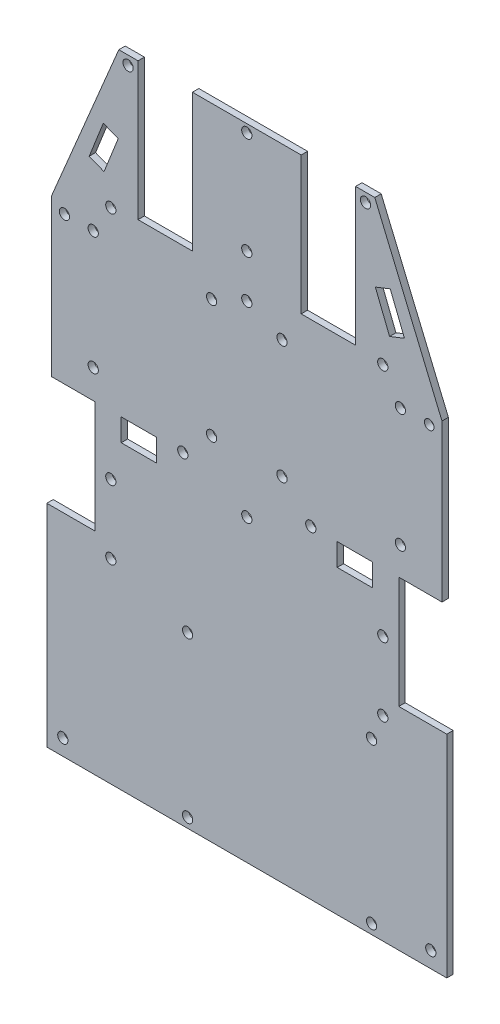
SolidWorks part; units mm, degrees
ref_plane "前基準面" through (0, 0, 0) normal (0, 0, 1) x (1, 0, 0)
ref_plane "上基準面" through (0, 0, 0) normal (0, 1, 0) x (1, 0, 0)
ref_plane "右基準面" through (0, 0, 0) normal (1, 0, 0) x (0, 0, -1)
sketch "草圖1" plane through (0, 0, 0) normal (0, 0, 1) x (1, 0, 0)
  line L0 (-42.5, 0) -> (42.5, 0)
  line L1 (-42.5, 0) -> (-42.5, 56)
  line L2 (-42.5, 56) -> (42.5, 56)
  line L3 (42.5, 56) -> (42.5, 0)
  line L4 (42.5, 0) -> (62.5, 0)
  line L5 (-42.5, 0) -> (-62.5, 0)
  line L6 (-62.5, 0) -> (-62.5, 66)
  line L7 (62.5, 0) -> (62.5, 66)
  line L8 (-62.5, 66) -> (-47.5, 66)
  line L9 (62.5, 66) -> (47.5, 66)
  line L10 (-47.5, 66) -> (-47.5, 101)
  line L12 (47.5, 101) -> (47.5, 66)
  line L16 (-62.5, 0) -> (-90.3643, 0)
  line L17 (-90.3643, 0) -> (-90.3643, 200)
  line L18 (-47.5, 101) -> (-61, 101)
  line L19 (47.5, 101) -> (61, 101)
  line L28 (-61, 101) -> (-61, 150)
  line L29 (-39.25, 101) -> (-28.25, 101)
  line L30 (39.25, 94) -> (28.25, 94)
  line L31 (-39.25, 101) -> (-39.25, 94)
  line L32 (-39.25, 94) -> (-28.25, 94)
  line L33 (-28.25, 101) -> (-28.25, 94)
  line L34 (28.25, 101) -> (28.25, 94)
  line L35 (39.25, 101) -> (28.25, 101)
  line L36 (39.25, 101) -> (39.25, 94)
  line L37 (61, 101) -> (61, 150)
  line L38 (62.5, 0) -> (90.3643, 0)
  line L39 (90.3643, 0) -> (90.3643, 200)
  line L40 (51, 107) -> (8, 107)
  line L41 (-51, 150) -> (-8, 150)
  line L42 (34, 200) -> (40, 200)
  line L43 (-51, 150) -> (-51, 107)
  line L44 (-51, 107) -> (-8, 107)
  line L45 (-8, 150) -> (-8, 107)
  line L46 (8, 150) -> (8, 107)
  line L47 (51, 150) -> (8, 150)
  line L48 (51, 150) -> (51, 107)
  line L49 (-17, 157) -> (-17, 200)
  line L50 (17, 157) -> (17, 200)
  line L52 (17, 157) -> (34, 157)
  line L53 (34, 157) -> (34, 200)
  line L54 (40, 200) -> (61, 150)
  line L55 (-90.3643, 200) -> (-40, 200)
  line L56 (-40, 200) -> (-61, 150)
  line L57 (-34, 200) -> (-40, 200)
  line L58 (-34, 157) -> (-34, 200)
  line L59 (-17, 157) -> (-34, 157)
  line L60 (-34, 200) -> (34, 200)
  line L62 (40, 200) -> (90.3643, 200)
  line L80 (62.5, 0) -> (62.5, -5)
  line L81 (-37.0994, 197.2091) -> (-56.9967, 147.0085) construction
  line L82 (37.0994, 197.2091) -> (56.9967, 147.0085) construction
  line L83 (-40.189, 175.8443) -> (-44.6106, 164.6886)
  line L84 (-40.189, 175.8443) -> (-44.8372, 177.6866)
  line L85 (-44.6106, 164.6886) -> (-49.2588, 166.5309)
  line L86 (-49.2588, 166.5309) -> (-44.8372, 177.6866)
  line L91 (40.189, 175.8443) -> (44.6106, 164.6886)
  line L92 (44.6106, 164.6886) -> (49.2588, 166.5309)
  line L93 (40.189, 175.8443) -> (44.8372, 177.6866)
  line L94 (44.8372, 177.6866) -> (49.2588, 166.5309)
  circle A0 centre (-48, 147) radius 1.6
  circle A1 centre (-48, 110) radius 1.6
  circle A2 centre (-11, 147) radius 1.6
  circle A3 centre (-11, 110) radius 1.6
  circle A4 centre (11, 147) radius 1.6
  circle A5 centre (47.9967, 147) radius 1.6
  circle A6 centre (47.9967, 110) radius 1.6
  circle A7 centre (11, 110) radius 1.6
  circle A10 centre (56.9967, 147.0085) radius 1.5
  circle A11 centre (37.0994, 197.2091) radius 1.6
  circle A12 centre (-56.9967, 147.0085) radius 1.6
  circle A13 centre (-37.0994, 197.2091) radius 1.6
  circle A16 centre (-18.5, 53) radius 1.6
  circle A17 centre (-18.5, 3) radius 1.6
  circle A18 centre (39, 53) radius 1.6
  circle A19 centre (39, 3) radius 1.6
  circle A22 centre (42.5, 61) radius 1.6
  circle A23 centre (-42.5, 61) radius 1.6
  circle A24 centre (0, 197.5) radius 1.6
  circle A25 centre (0, 165.5) radius 1.6
  circle A31 centre (42.5, 156) radius 1.6
  circle A32 centre (-42.5, 156) radius 1.6
  circle A33 centre (0, 93.5) radius 1.6
  circle A34 centre (57.5, 5) radius 1.6
  circle A35 centre (-57.5, 5) radius 1.6
  circle A36 centre (42.5, 82.5) radius 1.6
  circle A37 centre (-42.5, 82.5) radius 1.6
  circle A39 centre (-20, 101) radius 1.6
  circle A40 centre (20, 101) radius 1.6
  circle A45 centre (0, 152) radius 1.6
  point P4 (0, 0)
  point P57 (0, 0)
  dimension "D1" = 43
  dimension "D8" = 15
  dimension "D23" = 3.2
  dimension "D20" = 10
  dimension "D34" = 3.2
  dimension "D35" = 3.2
  dimension "D36" = 3.2
  dimension "D37" = 3.2
  dimension "D38" = 4.0033
  dimension "D39" = 3
  dimension "D40" = 37
  dimension "D41" = 3.2
  dimension "D42" = 3
  dimension "D43" = 37
  dimension "D44" = 3.2
  dimension "D45" = 3.2
  dimension "D46" = 3.2
  dimension "D47" = 3.2
  dimension "D48" = 3.2
  dimension "D49" = 3.2
  dimension "D54" = 3
  dimension "D56" = 3.2
  dimension "D59" = 3.2
  dimension "D61" = 3.2
  dimension "D62" = 3.2
  dimension "D64" = 3.2
  dimension "D67" = 85
  dimension "D73" = 3.2
  dimension "D74" = 3.2
  dimension "D72" = 3.2
  dimension "D80" = 12
  dimension "D78" = 61
  dimension "D82" = 3.2
  dimension "D83" = 3.2
  dimension "D87" = 3.2
  dimension "D88" = 3.2
  dimension "D92" = 3.2
  dimension "D93" = 3.2
  dimension "D96" = 5
  dimension "D2" = 43
  dimension "D3" = 85
  dimension "D4" = 56
  dimension "D5" = 66
  dimension "D6" = 20
  dimension "D7" = 20
  dimension "D9" = 35
  dimension "D10" = 8.25
  dimension "D11" = 8.25
  dimension "D12" = 13.5
  dimension "D13" = 49
  dimension "D14" = 54.231
  dimension "D15" = 50
  dimension "D16" = 50
  dimension "D17" = 6
  dimension "D18" = 43
  dimension "D19" = 17
  dimension "D21" = 3
  dimension "D22" = 24
  dimension "D24" = 57.5
  dimension "D25" = 50
  dimension "D26" = 10
  dimension "D27" = 7
  dimension "D28" = 11
  dimension "D29" = 6
  dimension "D30" = 38
  dimension "D31" = 11
  dimension "D32" = 38
  dimension "D33" = 7
  dimension "D50" = 3.0994
  dimension "D51" = 2.7909
  dimension "D52" = 3.0994
  dimension "D53" = 4.0033
  dimension "D55" = 46.0085
  dimension "D57" = 3
  dimension "D58" = 3
  dimension "D60" = 3
  dimension "D63" = 36.9967
  dimension "D65" = 47.5
  dimension "D66" = 6
  dimension "D68" = 8.5
  dimension "D69" = 37.5
  dimension "D70" = 34.5
  dimension "D71" = 2.5
  dimension "D75" = 20
  dimension "D76" = 20
  dimension "D77" = 5
  dimension "D79" = 5
  dimension "D81" = 5
  dimension "D84" = 41
  dimension "D85" = 41
  dimension "D86" = 6
  dimension "D89" = 20
  dimension "D90" = 20
  dimension "D91" = 26.5
  dimension "D94" = 5
  dimension "D95" = 5
  dimension "D97" = 21
  dimension "D98" = 5
  dimension "D99" = 12
  dimension "D100" = 21
extrude "填料-伸長1" add sketch "草圖1" along normal blind 2 contours L60 L49 L59 L58 L57 L56 L28 L18 L10 L8 L6 L5 L1 L2 L3 L4 L7 L9 L12 L19 L37 L54 L42 L53 L52 L50 A39 A35 A34 A33 A32 A31 A25 A24 A23 A22 A12 A11 | L45 L41 L43 L44 A3 A2 A1 A0 | L48 L47 L46 L40 A6 A4 A5 A7 | L3 L2 L1 L0 A17 A16 A18 A19
